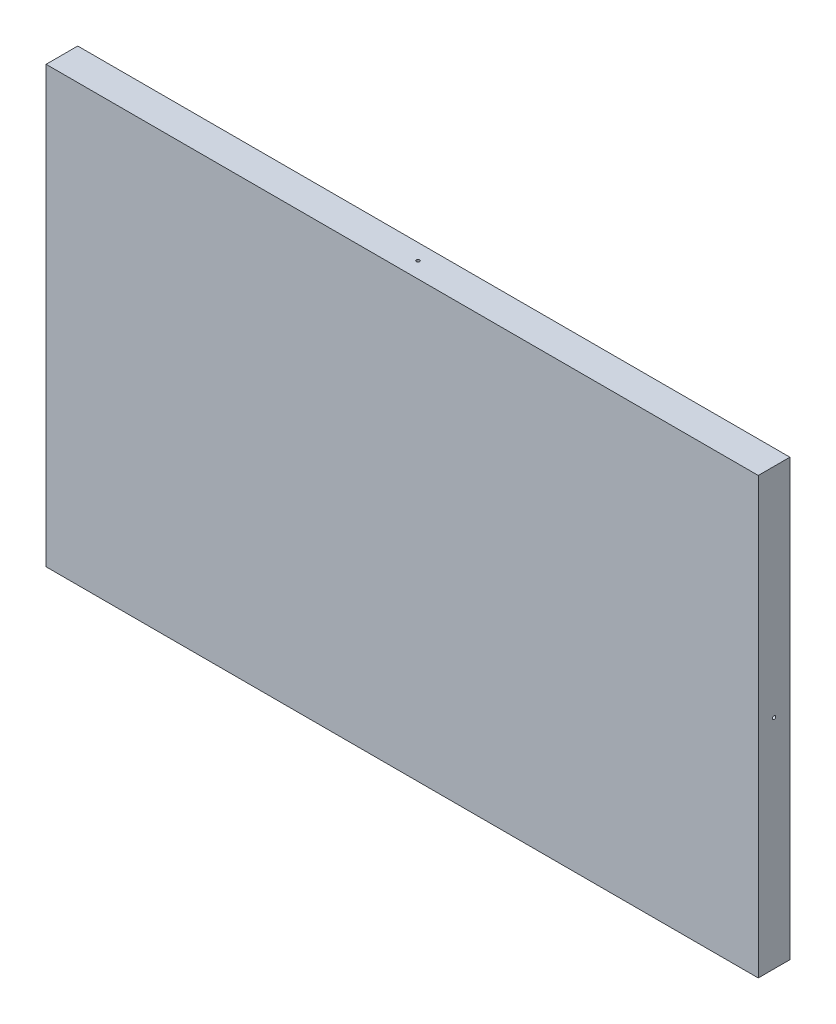
SolidWorks part; units mm, degrees
material "1.4511 (X3CrNb17)"
ref_plane "前视基准面" through (0, 0, 0) normal (0, 0, 1) x (1, 0, 0)
ref_plane "上视基准面" through (0, 0, 0) normal (0, 1, 0) x (1, 0, 0)
ref_plane "右视基准面" through (0, 0, 0) normal (1, 0, 0) x (0, 0, -1)
sketch "草图1" plane through (0, 0, 0) normal (0, 0, 1) x (1, 0, 0)
  line L1 (-450, 275) -> (450, 275)
  line L2 (-450, 275) -> (-450, -275)
  line L3 (-450, -275) -> (450, -275)
  line L4 (450, 275) -> (450, -275)
  line L5 (-450, 275) -> (450, -275) construction
  line L6 (-450, -275) -> (450, 275) construction
  point P0 (0, 0)
  dimension "D1" = 900
  dimension "D2" = 550
extrude "凸台-拉伸1" add sketch "草图1" along normal blind 40
sketch "草图2" plane through (0, 275, 0) normal (0, 1, 0) x (1, 0, 0)
  line L0 (-450, -40) -> (-450, 0) construction
  point P0 (0, -20)
  dimension "D1" = 450
hole_wizard "M5 螺纹孔1" positions "草图3" profile "草图4" tap size "M5" standard "GB" end condition through all
sketch "草图3" plane through (0, 275, 0) normal (0, 1, 0) x (1, 0, 0)
  point P0 (0, -20)
sketch "草图4" plane through (0, 275, 20) normal (1, 0, 0) x (0, 0, 1)
  line L0 (0, 0) -> (0, 550)
  line L1 (0, 550) -> (2.1, 550)
  line L2 (2.1, 550) -> (2.1, 0)
  line L5 (2.1, 0) -> (0, 0)
  line L11 (0, -6.35) -> (0, 107.95) construction
  dimension "通孔螺纹孔钻头直径" = 4.2
  dimension "通孔螺纹孔钻头深度" = 550
cosmetic thread "孔螺蚊线1" parameters "D2"=5
sketch "草图5" plane through (-450, 0, 0) normal (-1, 0, 0) x (0, 0, 1)
  line L0 (40, 275) -> (0, 275) construction
  point P0 (20, 0)
  dimension "D1" = 275
hole_wizard "M5 螺纹孔2" positions "草图6" profile "草图7" tap size "M5" standard "GB" end condition through all
sketch "草图6" plane through (-450, 0, 0) normal (-1, 0, 0) x (0, 0, 1)
  point P0 (20, 0)
sketch "草图7" plane through (-450, 0, 20) normal (0, 1, 0) x (0, 0, 1)
  line L0 (0, 0) -> (0, 900)
  line L1 (0, 900) -> (2.1, 900)
  line L2 (2.1, 900) -> (2.1, 0)
  line L5 (2.1, 0) -> (0, 0)
  line L11 (0, -6.35) -> (0, 107.95) construction
  dimension "通孔螺纹孔钻头直径" = 4.2
  dimension "通孔螺纹孔钻头深度" = 900
cosmetic thread "孔螺蚊线2" parameters "D2"=5
